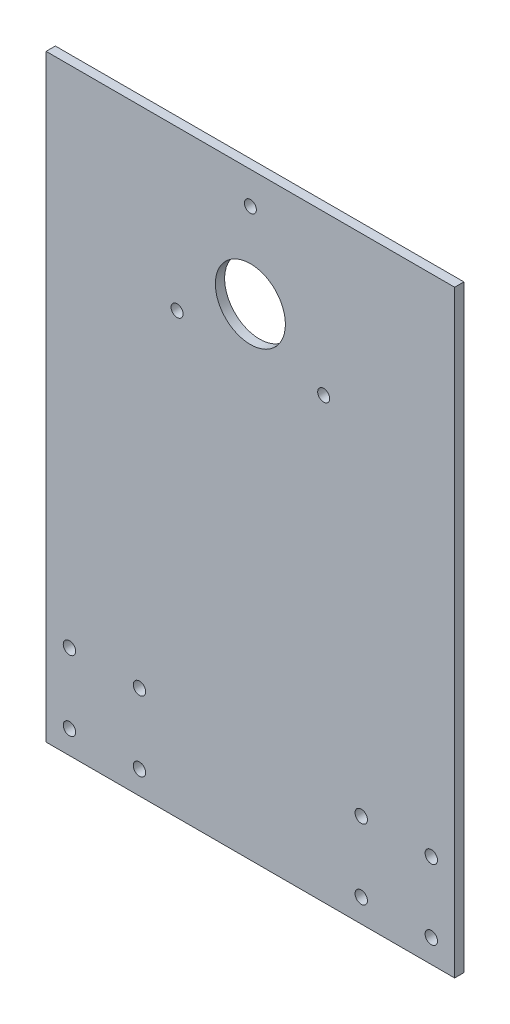
SolidWorks part; units mm, degrees
ref_plane "Front Plane" through (0, 0, 0) normal (0, 0, 1) x (1, 0, 0)
ref_plane "Top Plane" through (0, 0, 0) normal (0, 1, 0) x (1, 0, 0)
ref_plane "Right Plane" through (0, 0, 0) normal (1, 0, 0) x (0, 0, -1)
sketch "Sketch1" plane through (0, 0, 0) normal (0, 0, 1) x (1, 0, 0)
  line L0 (0, 102.5) -> (0, -102.5) construction
  line L1 (-70, -102.5) -> (70, -102.5)
  line L2 (-70, -102.5) -> (-70, 102.5)
  line L3 (-70, 102.5) -> (70, 102.5)
  line L4 (70, -102.5) -> (70, 102.5)
  line L5 (-70, -102.5) -> (70, 102.5) construction
  line L6 (-70, 102.5) -> (70, -102.5) construction
  line L7 (-50, -98.3304) -> (-50, -80.5714) construction
  line L10 (-62, -82.5) -> (-36.3402, -82.5) construction
  circle A0 centre (0, 62.5) radius 33.35 construction
  circle A1 centre (0, 62.5) radius 29 construction
  circle A2 centre (0, 91.5) radius 2.05
  circle A3 centre (25.1147, 48) radius 2.05
  circle A4 centre (-25.1147, 48) radius 2.05
  circle A10 centre (0, 62.5) radius 12
  circle A11 centre (-62, -94.5) radius 2.125
  circle A12 centre (-38, -94.5) radius 2.125
  circle A13 centre (-38, -70.5) radius 2.125
  circle A14 centre (-62, -70.5) radius 2.125
  circle A15 centre (38, -94.5) radius 2.125
  circle A16 centre (62, -94.5) radius 2.125
  circle A17 centre (62, -70.5) radius 2.125
  circle A18 centre (38, -70.5) radius 2.125
  point P0 (0, 0)
  point P19 (0, 62.5)
  dimension "D3" = 66.7
  dimension "D4" = 40
  dimension "D5" = 58
  dimension "D6" = 4.1
  dimension "D8" = 4.25
  dimension "D9" = 8
  dimension "D10" = 8
  dimension "D12" = 24
  dimension "D1" = 140
  dimension "D2" = 205
  dimension "D11" = 12
  dimension "D13" = 12
  dimension "D7" = 3
extrude "Boss-Extrude1" add sketch "Sketch1" along normal blind 3.175
